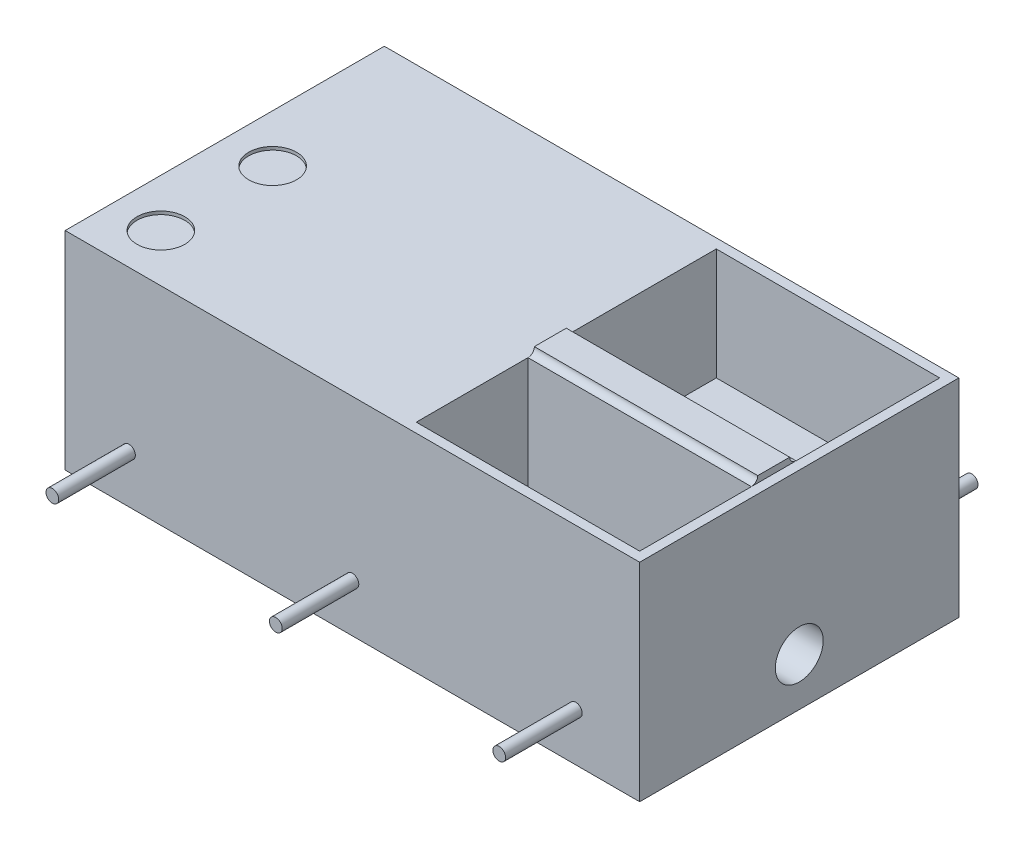
SolidWorks part; units mm, degrees
ref_plane "Ebene vorne" through (0, 0, 0) normal (0, 0, 1) x (1, 0, 0)
ref_plane "Ebene oben" through (0, 0, 0) normal (0, 1, 0) x (1, 0, 0)
ref_plane "Ebene rechts" through (0, 0, 0) normal (1, 0, 0) x (0, 0, -1)
sketch "Skizze1" plane through (0, 0, 0) normal (0, 1, 0) x (1, 0, 0)
  line L1 (-900, 500) -> (900, 500)
  line L2 (-900, 500) -> (-900, -500)
  line L3 (-900, -500) -> (900, -500)
  line L4 (900, 500) -> (900, -500)
  line L5 (-900, 500) -> (900, -500) construction
  line L6 (-900, -500) -> (900, 500) construction
  point P0 (0, 0)
  dimension "D1" = 1000
  dimension "D2" = 1800
extrude "Aufsatz-Linear austragen1" add sketch "Skizze1" against normal blind 650
sketch "Skizze2" plane through (0, 0, 0) normal (0, 0, 1) x (1, 0, 0)
  line L0 (-900, -500) -> (900, -500) construction
  line L1 (-900, -650) -> (-900, 0) construction
  line L2 (900, -650) -> (900, 0) construction
  line L3 (-900, -650) -> (900, -650) construction
  line L4 (0, -357.5) -> (0, 357.5) construction
  circle A0 centre (0, -500) radius 20
  circle A1 centre (-700, -500) radius 20
  circle A2 centre (700, -500) radius 20
  dimension "D2" = 40
  dimension "D4" = 40
  dimension "D1" = 150
  dimension "D3" = 200
extrude "Aufsatz-Linear austragen2" add sketch "Skizze2" along normal blind 740 and the other way blind 740
sketch "Skizze3" plane through (0, 0, 0) normal (0, 1, 0) x (1, 0, 0)
  line L0 (900, 500) -> (-900, 500) construction
  line L1 (870, 470) -> (170, 470)
  line L2 (870, 470) -> (870, 20)
  line L3 (870, 20) -> (170, 20)
  line L4 (170, 470) -> (170, 20)
  line L5 (170, -120) -> (870, -120)
  line L6 (170, -120) -> (170, -470)
  line L7 (170, -470) -> (870, -470)
  line L8 (870, -120) -> (870, -470)
  line L9 (900, -500) -> (900, 500) construction
  line L10 (-900, -500) -> (900, -500) construction
  dimension "D1" = 30
  dimension "D2" = 30
  dimension "D3" = 30
  dimension "D4" = 30
  dimension "D5" = 700
  dimension "D6" = 700
  dimension "D7" = 350
  dimension "D8" = 450
extrude "Schnitt-Linear austragen1" cut sketch "Skizze3" against normal blind 350
sketch "Skizze4" plane through (0, 0, 0) normal (0, 1, 0) x (1, 0, 0)
  line L1 (170, 20) -> (870, 20)
  line L2 (170, 20) -> (170, -120)
  line L3 (170, -120) -> (870, -120)
  line L4 (870, 20) -> (870, -120)
extrude "Aufsatz-Linear austragen3" add sketch "Skizze4" along normal blind 20
sketch "Skizze5" plane through (870, 0, 0) normal (1, 0, 0) x (0, 0, -1)
  circle A0 centre (-120, 20) radius 20
  circle A1 centre (20, 20) radius 20
  dimension "D1" = 40
  dimension "D2" = 40
extrude "Schnitt-Linear austragen2" cut sketch "Skizze5" against normal up to surface (700 mm away) up to face at (170, 10, 50)
sketch "Skizze6" plane through (900, 0, 0) normal (1, 0, 0) x (0, 0, -1)
  line L0 (-500, -500) -> (500, -500) construction
  line L1 (-500, -650) -> (-500, 0) construction
  line L2 (500, -650) -> (500, 0) construction
  line L3 (-500, -650) -> (500, -650) construction
  circle A0 centre (0, -500) radius 75
  dimension "D2" = 150
  dimension "D1" = 150
extrude "Schnitt-Linear austragen3" cut sketch "Skizze6" against normal up to surface (1800 mm away) up to face at (-900, -325, 0)
sketch "Skizze7" plane through (0, 0, 0) normal (0, 1, 0) x (1, 0, 0)
  line L0 (-900, 500) -> (-900, -500) construction
  line L1 (-900, -500) -> (900, -500) construction
  circle A0 centre (-750, -350) radius 75
  dimension "D2" = 150
  dimension "D1" = 150
  dimension "D3" = 150
extrude "Schnitt-Linear austragen4" cut sketch "Skizze7" against normal blind 10
sketch "Skizze8" plane through (0, 0, 0) normal (0, 1, 0) x (1, 0, 0)
  line L0 (-900, 500) -> (-900, -500) construction
  line L1 (900, 500) -> (-900, 500) construction
  circle A0 centre (-750, 0) radius 75
  dimension "D1" = 150
  dimension "D2" = 150
  dimension "D3" = 500
extrude "Schnitt-Linear austragen5" cut sketch "Skizze8" against normal blind 10
